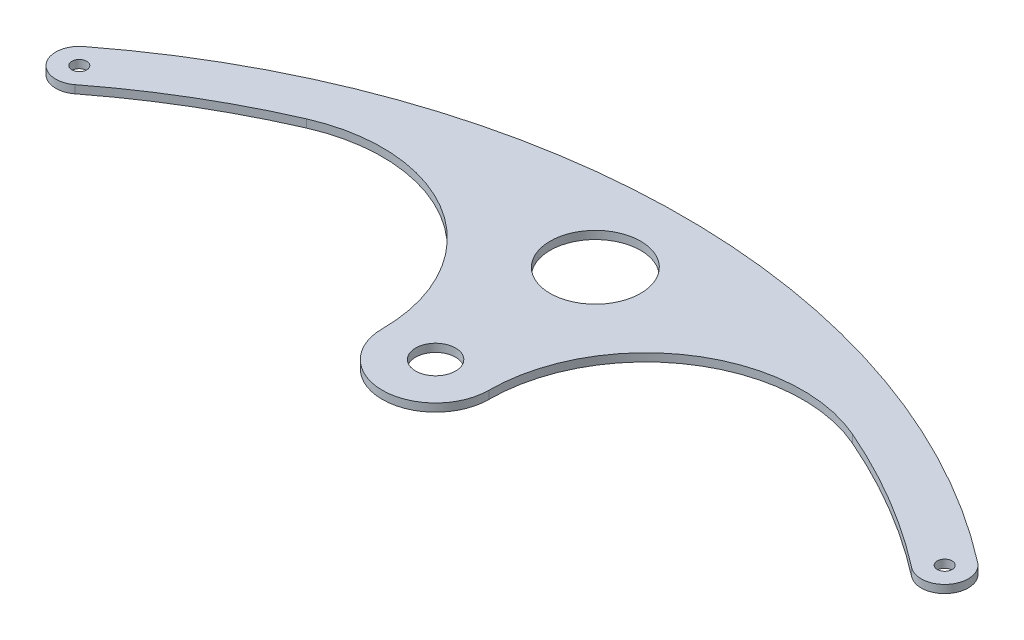
SolidWorks part; units mm, degrees
ref_plane "Front Plane" through (0, 0, 0) normal (0, 0, 1) x (1, 0, 0)
ref_plane "Top Plane" through (0, 0, 0) normal (0, 1, 0) x (1, 0, 0)
ref_plane "Right Plane" through (0, 0, 0) normal (1, 0, 0) x (0, 0, -1)
sketch "Sketch1" plane through (0, 0, 0) normal (0, 1, 0) x (1, 0, 0)
  line L0 (3.048, 4.191) -> (3.048, -6.604) construction
  line L1 (0, 0) -> (206.375, 0) construction
  line L2 (103.1875, 0) -> (103.1875, 50.9033) construction
  line L3 (47.625, 0) -> (47.625, 19.05) construction
  line L4 (60.3023, -7.112) -> (162.9473, -7.112) construction
  line L5 (60.3023, -18.2245) -> (162.9473, -18.2245) construction
  line L6 (103.1875, 0) -> (103.1875, -18.2245) construction
  circle A0 centre (0, 0) radius 1.778
  circle A1 centre (206.375, 0) radius 1.778
  arc A3 (-3.435, 4.439) -> (3.435, -4.439) centre (0, 0) ccw
  arc A4 (209.81, 4.439) -> (202.94, -4.439) centre (206.375, 0) cw
  arc A5 (202.94, -4.439) -> (168.2637, 16.0946) centre (103.1875, -133.35) ccw
  arc A6 (209.81, 4.439) -> (-3.435, 4.439) centre (103.1875, -133.35) ccw
  circle A7 centre (103.1875, -18.2245) radius 4.7625
  arc A8 (90.4875, -18.2245) -> (115.8875, -18.2245) centre (103.1875, -18.2245) ccw
  arc A9 (90.4875, -18.2245) -> (38.1113, 16.0946) centre (53.0557, -18.2245) ccw
  arc A10 (115.8875, -18.2245) -> (168.2637, 16.0946) centre (153.3193, -18.2245) cw
  arc A11 (38.1113, 16.0946) -> (3.435, -4.439) centre (103.1875, -133.35) ccw
  circle A12 centre (103.1875, 19.8755) radius 10.795
  dimension "D2" = 3.556
  dimension "D3" = 3.556
  dimension "D12" = 9.525
  dimension "D13" = 25.4
  dimension "D14" = 74.8636
  dimension "D15" = 21.59
  dimension "D1" = 206.375
  dimension "D5" = 3.048
  dimension "D6" = 6.604
  dimension "D7" = 47.625
  dimension "D8" = 19.05
  dimension "D9" = 133.35
  dimension "D10" = 7.112
  dimension "D11" = 11.1125
  dimension "D16" = 38.1
extrude "Boss-Extrude1" add sketch "Sketch1" along normal blind 1.905 contours A6 A3 A11 A9 A8 A10 A5 A4
